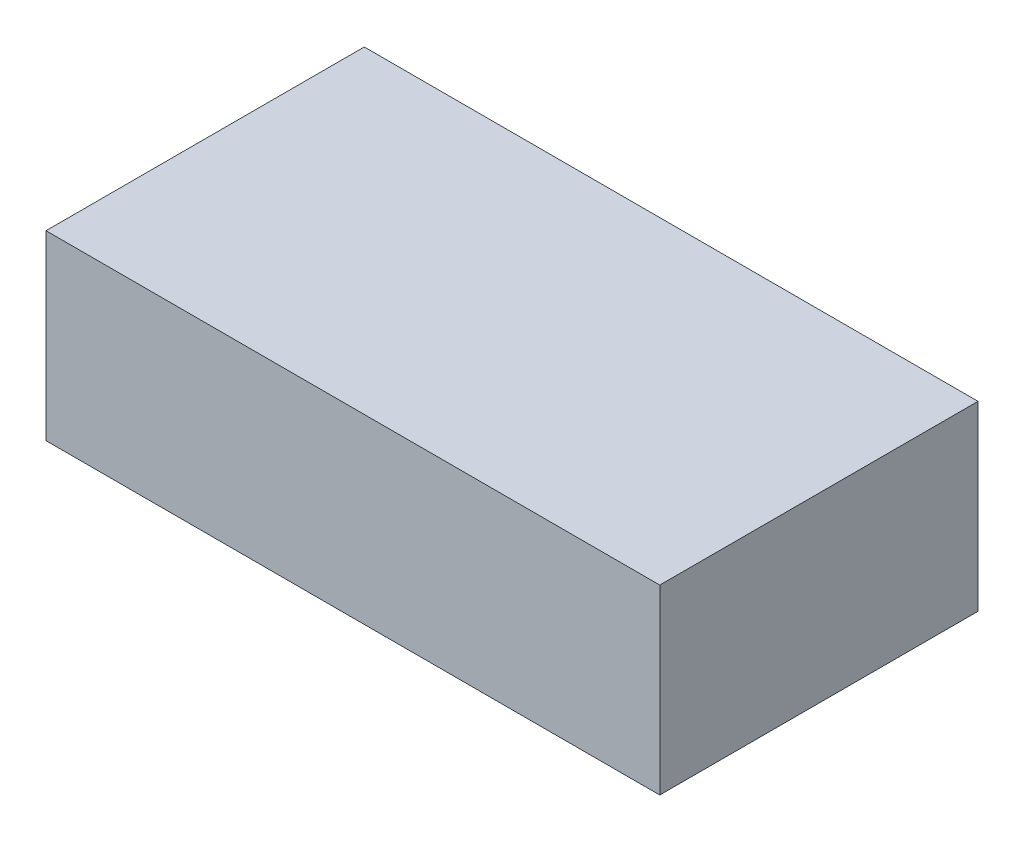
SolidWorks part; units mm, degrees
material "ABS"
ref_plane "Front Plane" through (0, 0, 0) normal (0, 0, 1) x (1, 0, 0)
ref_plane "Top Plane" through (0, 0, 0) normal (0, 1, 0) x (1, 0, 0)
ref_plane "Right Plane" through (0, 0, 0) normal (1, 0, 0) x (0, 0, -1)
other "Configuration Table"
sketch "Sketch1" plane through (0, 0, 0) normal (0, 1, 0) x (1, 0, 0)
  line L1 (-13.5, -7) -> (13.5, -7)
  line L2 (-13.5, -7) -> (-13.5, 7)
  line L3 (-13.5, 7) -> (13.5, 7)
  line L4 (13.5, -7) -> (13.5, 7)
  line L5 (-13.5, -7) -> (13.5, 7) construction
  line L6 (-13.5, 7) -> (13.5, -7) construction
  point P6 (0, 0)
  dimension "D1" = 27
  dimension "D2" = 14
extrude "Housing" add sketch "Sketch1" along normal blind 8
equation "\"Jar_OD\"= 90  'ASSUMED - Part G fallback - jar outer diameter"
equation "\"Jar_H\"= 120  'ASSUMED - Part G fallback - jar height"
equation "\"Pump_L\"= 45  'ASSUMED - Part G fallback"
equation "\"Pump_W\"= 24  'ASSUMED - Part G fallback"
equation "\"Pump_H\"= 33  'ASSUMED - Part G fallback"
equation "\"Pump_Outlet_OD\"= 7.5  'ASSUMED - Part G fallback"
equation "\"Tube_OD\"= 8  'ASSUMED - Part G fallback"
equation "\"Tube_ID\"= 6  'ASSUMED - Part G fallback"
equation "\"TDS_Body_Dia\"= 12  'ASSUMED - Part G fallback"
equation "\"TDS_Wet_Len\"= 45  'ASSUMED - Part G fallback - length in water"
equation "\"DS_Tube_Dia\"= 6  'ASSUMED - Part G fallback"
equation "\"DS_Tube_Len\"= 50  'ASSUMED - Part G fallback"
equation "\"ORP_Body_Dia\"= 12  'ASSUMED - Part G fallback"
equation "\"ORP_Body_Len\"= 150  'ASSUMED - Part G fallback"
equation "\"ORP_Cap_Dia\"= 16  'ASSUMED - Part G fallback"
equation "\"Turb_W\"= 33  'ASSUMED - Part G fallback - head width"
equation "\"Turb_D\"= 28  'ASSUMED - Part G fallback - head depth"
equation "\"Turb_H\"= 30  'ASSUMED - Part G fallback - head height"
equation "\"Turb_Slot_W\"= 10  'ASSUMED - Part G fallback - slot width"
equation "\"Flow_L\"= 62  'ASSUMED - Part G fallback YF-S201"
equation "\"Flow_W\"= 36  'ASSUMED - Part G fallback"
equation "\"Flow_H\"= 35  'ASSUMED - Part G fallback"
equation "\"Thread_G12_OD\"= 20.955  'ASSUMED - Part G fallback thread G1/2 (major diameter)"
equation "\"Valve_L\"= 75  'ASSUMED - Part G fallback"
equation "\"Valve_W\"= 45  'ASSUMED - Part G fallback"
equation "\"Valve_H\"= 60  'ASSUMED - Part G fallback"
equation "\"Tee_L\"= 40  'ASSUMED - Part G fallback - overall length"
equation "\"Tee_Branch_L\"= 25  'ASSUMED - Part G fallback"
equation "\"Tee_OD\"= 12  'ASSUMED - Part G fallback"
equation "\"Cuv_W\"= 12.5  'ASSUMED - old R3 cuvette (station suppressed in SS4)"
equation "\"Cuv_D\"= 12.5  'ASSUMED - old R3 cuvette (station suppressed in SS4)"
equation "\"Cuv_H\"= 45  'ASSUMED - old R3 cuvette (station suppressed in SS4)"
equation "\"LED_Board_L\"= 20  'ASSUMED - Part G fallback"
equation "\"LED_Board_W\"= 20  'ASSUMED - Part G fallback - LED at centre"
equation "\"GUVA_L\"= 20  'ASSUMED - Part G fallback"
equation "\"GUVA_W\"= 12  'ASSUMED - Part G fallback - sensor at centre"
equation "\"Reed_L\"= 27  'ASSUMED - Part G fallback MC-38 half"
equation "\"Reed_W\"= 14  'ASSUMED - Part G fallback"
equation "\"Reed_H\"= 8  'ASSUMED - Part G fallback"
equation "\"ESP_L\"= 51  'ASSUMED - Part G fallback"
equation "\"ESP_W\"= 28  'ASSUMED - Part G fallback"
equation "\"TFT_L\"= 58  'ASSUMED - Part G fallback - board"
equation "\"TFT_W\"= 35  'ASSUMED - Part G fallback - board"
equation "\"TFT_Win_L\"= 35  'ASSUMED - Part G fallback - visible window"
equation "\"TFT_Win_W\"= 28  'ASSUMED - Part G fallback - visible window"
equation "\"Relay_L\"= 50  'ASSUMED - Part G fallback"
equation "\"Relay_W\"= 26  'ASSUMED - Part G fallback"
equation "\"Relay_H\"= 19  'ASSUMED - Part G fallback"
equation "\"Mosfet_L\"= 34  'ASSUMED - Part G fallback"
equation "\"Mosfet_W\"= 17  'ASSUMED - Part G fallback"
equation "\"Mosfet_H\"= 12  'ASSUMED - Part G fallback"
equation "\"TDS_Board_L\"= 42  'ASSUMED - Part G fallback"
equation "\"TDS_Board_W\"= 32  'ASSUMED - Part G fallback"
equation "\"Turb_Board_L\"= 38  'ASSUMED - Part G fallback"
equation "\"Turb_Board_W\"= 28  'ASSUMED - Part G fallback"
equation "\"BNC_Thread_Dia\"= 9.5  'ASSUMED - Part G fallback"
equation "\"Plate_L\"= 420  'ASSUMED - Part G fallback"
equation "\"Plate_W\"= 297  'ASSUMED - Part G fallback"
equation "\"Plate_T\"= 6  'ASSUMED - Part G fallback"
equation "\"Probe_Clr\"= 0.3  'DESIGN VALUE - Part C rule 3 - printed probe hole = diameter + 0.3"
equation "\"Cuv_Clr\"= 0.2  'DESIGN VALUE - Part C rule 3 - cuvette pocket = size + 0.2"
equation "\"Label_H\"= 0.6  'DESIGN VALUE - Part D - raised label height"
equation "\"D1@Sketch1\" = \"Reed_L\""
equation "\"D2@Sketch1\" = \"Reed_W\""
equation "\"D1@Housing\" = \"Reed_H\""
equation "\"Booster_L\"= 150  'ASSUMED - Part G fallback - booster pump"
equation "\"Booster_W\"= 95  'ASSUMED - Part G fallback"
equation "\"Booster_H\"= 100  'ASSUMED - Part G fallback"
equation "\"PTube_OD\"= 6.35  'ASSUMED - Part G fallback - product tube 1/4 inch"
equation "\"Qz_Out\"= 12  'ASSUMED - Part G fallback - quartz channel outside square"
equation "\"Qz_Path\"= 10  'ASSUMED - Part G fallback - quartz channel inside light path"
equation "\"Qz_L\"= 40  'ASSUMED - Part G fallback - quartz channel length"
equation "\"LED860_Dia\"= 5  'ASSUMED - Part G fallback - 860 nm LED"
equation "\"BPW_L\"= 5.4  'ASSUMED - Part G fallback - BPW34"
equation "\"BPW_W\"= 4.3  'ASSUMED - Part G fallback - BPW34"
equation "\"Cart_Dia\"= 50  'ASSUMED - Part G fallback - sediment and pre-carbon cartridges"
equation "\"Cart_L\"= 255  'ASSUMED - Part G fallback"
equation "\"UF_Dia\"= 50  'ASSUMED - Part G fallback - UF cartridge"
equation "\"UF_L\"= 260  'ASSUMED - Part G fallback"
equation "\"RO_Dia\"= 62  'ASSUMED - Part G fallback - RO membrane housing"
equation "\"RO_L\"= 300  'ASSUMED - Part G fallback"
equation "\"UVC_Dia\"= 40  'ASSUMED - Part G fallback - UV-C chamber"
equation "\"UVC_L\"= 300  'ASSUMED - Part G fallback"
equation "\"Tank_W\"= 260  'ASSUMED - Part G fallback - storage tank"
equation "\"Tank_D\"= 160  'ASSUMED - Part G fallback"
equation "\"Tank_H\"= 300  'ASSUMED - Part G fallback"
equation "\"Cab_W\"= 400  'ASSUMED - Part G fallback - purifier cabinet"
equation "\"Cab_D\"= 270  'ASSUMED - Part G fallback"
equation "\"Cab_H\"= 560  'ASSUMED - Part G fallback"
equation "\"ORP_Board_L\"= 40  'ASSUMED - Part G fallback - ORP buffer board"
equation "\"ORP_Board_W\"= 30  'ASSUMED - Part G fallback"
equation "\"Opt_Board_L\"= 50  'ASSUMED - Part G fallback - optical front-end board"
equation "\"Opt_Board_W\"= 40  'ASSUMED - Part G fallback"
equation "\"Buck_L\"= 43  'ASSUMED - Part G fallback - 12 V to 5 V buck module"
equation "\"Buck_W\"= 21  'ASSUMED - Part G fallback"
equation "\"Buck_H\"= 14  'ASSUMED - Part G fallback"
equation "\"BB_L\"= 165  'ASSUMED - Part G fallback - breadboard (As_Built_R3 only)"
equation "\"BB_W\"= 55  'ASSUMED - Part G fallback"
equation "\"BB_H\"= 10  'ASSUMED - Part G fallback"
